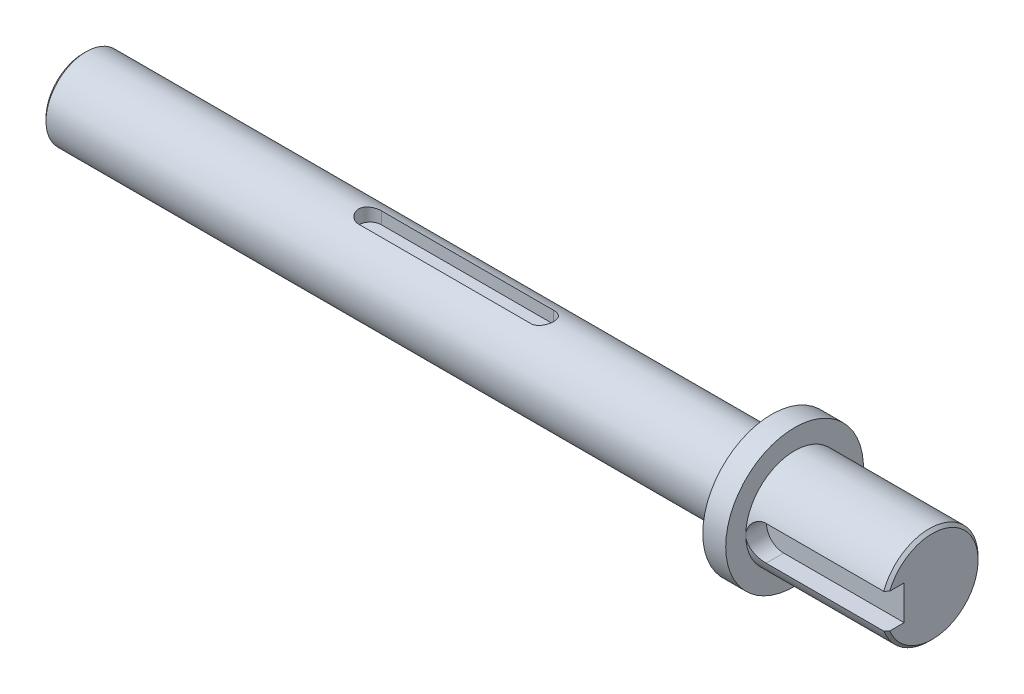
SolidWorks part; units mm, degrees
material "Galvanized Steel"
ref_plane "Front Plane" through (0, 0, 0) normal (0, 0, 1) x (1, 0, 0)
ref_plane "Top Plane" through (0, 0, 0) normal (0, 1, 0) x (1, 0, 0)
ref_plane "Right Plane" through (0, 0, 0) normal (1, 0, 0) x (0, 0, -1)
ref_plane "2x2 Keyway Plane" through (0, 3.5, 0) normal (0, 1, 0) x (-1, 0, 0)
ref_plane "3x3 Keyway Plane" through (0, 0, 4.25) normal (0, 0, 1) x (1, 0, 0)
sketch "Sketch1" plane through (0, 0, 0) normal (1, 0, 0) x (0, 0, -1)
  circle A0 centre (0, 0) radius 3.5
  dimension "D1" = 7
extrude "Shaft-Boss" add sketch "Sketch1" along normal blind 60
sketch "Sketch2" plane through (0, 3.5, 0) normal (0, 1, 0) x (-1, 0, 0)
  line L0 (-25, 0) -> (-40, 0) construction
  line L1 (-25, -1) -> (-40, -1)
  line L2 (-25, 1) -> (-40, 1)
  line L3 (0, -3.5) -> (0, 3.5) construction
  arc A0 (-25, -1) -> (-25, 1) centre (-25, 0) ccw
  arc A1 (-40, 1) -> (-40, -1) centre (-40, 0) ccw
  point P3 (-32.5, 0)
  dimension "D1" = 15
  dimension "D2" = 25
  dimension "D3" = 2
extrude "Cut-2x2 Keyway" cut sketch "Sketch2" against normal blind 1.2
sketch "Sketch3" plane through (60, 0, 0) normal (1, 0, 0) x (0, 0, -1)
  circle A0 centre (0, 0) radius 6
  dimension "D1" = 12
extrude "Collar-Boss" add sketch "Sketch3" along normal blind 2
sketch "Sketch4" plane through (62, 0, 0) normal (1, 0, 0) x (0, 0, -1)
  circle A0 centre (0, 0) radius 4.25
  dimension "D1" = 8.5
extrude "Handle-Boss" add sketch "Sketch4" along normal blind 12
sketch "Sketch5" plane through (0, 0, 4.25) normal (0, 0, 1) x (1, 0, 0)
  line L0 (83.5, 0) -> (63.5, 0) construction
  line L1 (83.5, -1.5) -> (63.5, -1.5)
  line L2 (83.5, 1.5) -> (63.5, 1.5)
  line L3 (62, -6) -> (62, 6) construction
  arc A0 (83.5, -1.5) -> (83.5, 1.5) centre (83.5, 0) ccw
  arc A1 (63.5, 1.5) -> (63.5, -1.5) centre (63.5, 0) ccw
  point P3 (73.5, 0)
  dimension "D1" = 3
  dimension "D2" = 20
  dimension "D3" = 1.5
extrude "Cut-3x3 Keyway" cut sketch "Sketch5" against normal blind 1.8
chamfer "Chamfer1" distance 0.254 angle 45 2 edges at (74, 0, -4.25) (0, 0, -3.5)
